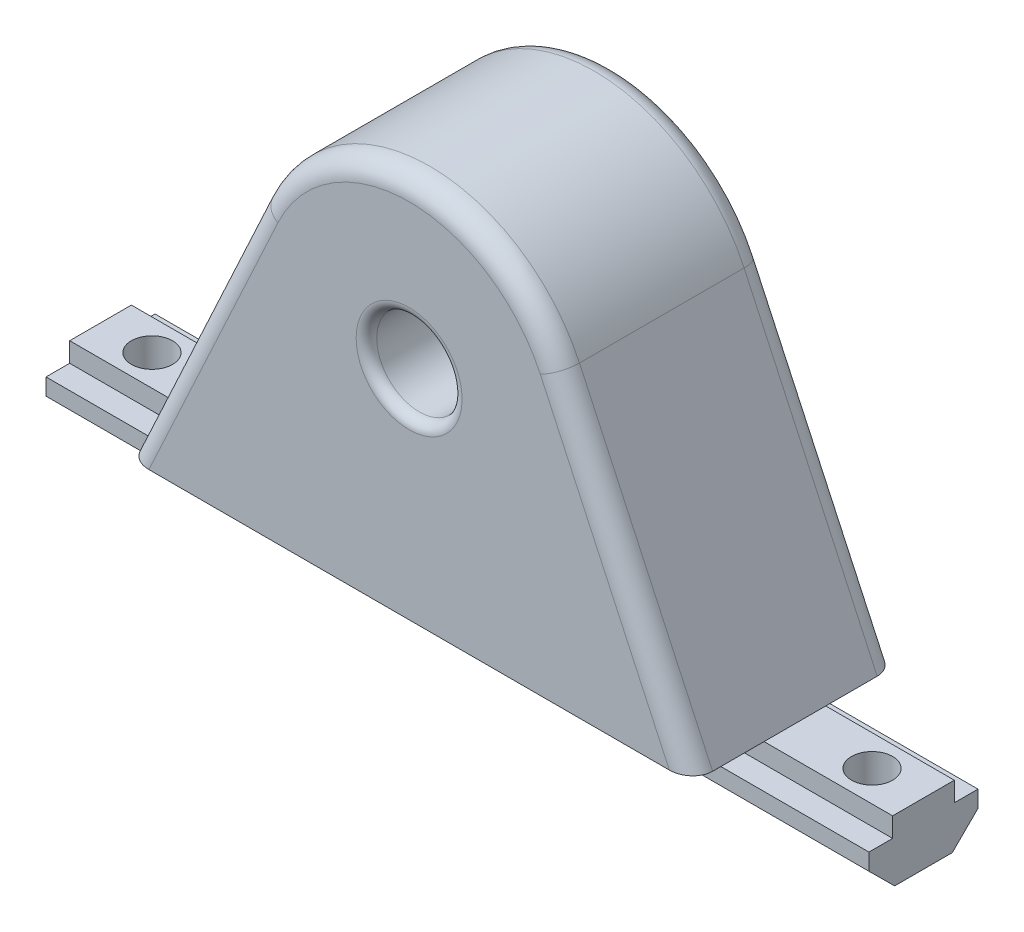
SolidWorks part; units mm, degrees
ref_plane "Front (XY)" through (0, 0, 0) normal (0, 0, 1) x (1, 0, 0)
ref_plane "Top (XZ)" through (0, 0, 0) normal (0, 1, 0) x (1, 0, 0)
ref_plane "Right (YZ)" through (0, 0, 0) normal (1, 0, 0) x (0, 0, -1)
sketch "Sketch1" plane through (0, 0, 0) normal (1, 0, 0) x (0, 0, -1)
  line L31 (0, 0) -> (0, 6) construction
  line L32 (-3, 6) -> (3, 6)
  line L33 (-3, 6) -> (-3, 4.1)
  line L34 (3, 6) -> (3, 4.1)
  line L35 (-3, 4.1) -> (-5.3, 4.1)
  line L36 (3, 4.1) -> (5.3, 4.1)
  line L37 (-5.3, 4.1) -> (-5.3, 2.48)
  line L38 (5.3, 4.1) -> (5.3, 2.48)
  line L39 (-2.8, 0) -> (2.8, 0)
  line L40 (-2.8, 0) -> (-5.3, 2.48)
  line L41 (2.8, 0) -> (5.3, 2.48)
  point P31 (0, 6)
  point P40 (0, 0)
  dimension "D1" = 6
  dimension "D2" = 1.9
  dimension "D3" = 1.62
  dimension "D4" = 5.6
  dimension "D5" = 6
  dimension "D6" = 2.3
extrude "Boss-Extrude1" add sketch "Sketch1" along normal mid plane 80
sketch "Sketch2" plane through (0, 0, 0) normal (0, 0, 1) x (1, 0, 0)
  line L0 (0, 0) -> (0, 50) construction
  line L1 (40, 6) -> (-40, 6) construction
  line L2 (27.5, 6) -> (-27.5, 6)
  line L3 (-27.5, 6) -> (-27.5, 50)
  line L4 (-27.5, 50) -> (27.5, 50)
  line L5 (27.5, 50) -> (27.5, 6)
  dimension "D2" = 55
  dimension "D1" = 50
  dimension "D3" = 27.5
extrude "Boss-Extrude2" add sketch "Sketch2" along normal mid plane 20
sketch "Sketch3" plane through (0, 0, 0) normal (0, 0, 1) x (1, 0, 0)
  line L0 (0, 0) -> (0, 27.15) construction
  circle A0 centre (0, 27.15) radius 4.15
  dimension "D2" = 8.3
  dimension "D1" = 27.15
extrude "Cut-Extrude2" cut sketch "Sketch3" against normal through all both and the other way through all
sketch "Sketch6" plane through (0, 0, 0) normal (0, 0, 1) x (1, 0, 0)
  circle A1 centre (0, 27.15) radius 11.05
  dimension "D1" = 22.1
sketch "Sketch7" plane through (0, 0, 0) normal (0, 0, 1) x (1, 0, 0)
  line L0 (27.5, 6) -> (14.5605, 33.9023)
  line L1 (-27.5, 6) -> (-14.5605, 33.9023)
  line L2 (-27.5, 6) -> (-40, 6)
  line L3 (-40, 6) -> (-40, 58.2978)
  line L4 (40, 6) -> (27.5, 6) construction
  line L5 (40, 6) -> (27.5, 6)
  line L6 (-40, 58.2978) -> (40, 58.2978)
  line L7 (40, 58.2978) -> (40, 6)
  circle A2 centre (0, 27.15) radius 16.05
  arc A3 (14.5605, 33.9023) -> (-14.5605, 33.9023) centre (0, 27.15) ccw
  dimension "D1" = 5
extrude "Cut-Extrude3" cut sketch "Sketch7" against normal through all both and the other way through all
extrude "Cut-Extrude4" cut sketch "Sketch6" against normal through all
fillet "Fillet1" radius 2 6 edges at (21.0303, 19.9512, 10) (0, 43.2, 10) (-21.0303, 19.9512, 10) (-21.0303, 19.9512, -10) (0, 43.2, -10) (21.0303, 19.9512, -10)
fillet "Fillet2" radius 1 2 edges at (4.15, 27.15, 0) (4.15, 27.15, 10)
sketch "Sketch8" plane through (0, 6, 0) normal (0, 1, 0) x (1, 0, 0)
  circle A0 centre (35, 0) radius 2
  circle A1 centre (-35, 0) radius 2
  dimension "D1" = 4
  dimension "D2" = 35
  dimension "D3" = 35
extrude "Cut-Extrude5" cut sketch "Sketch8" against normal through all
